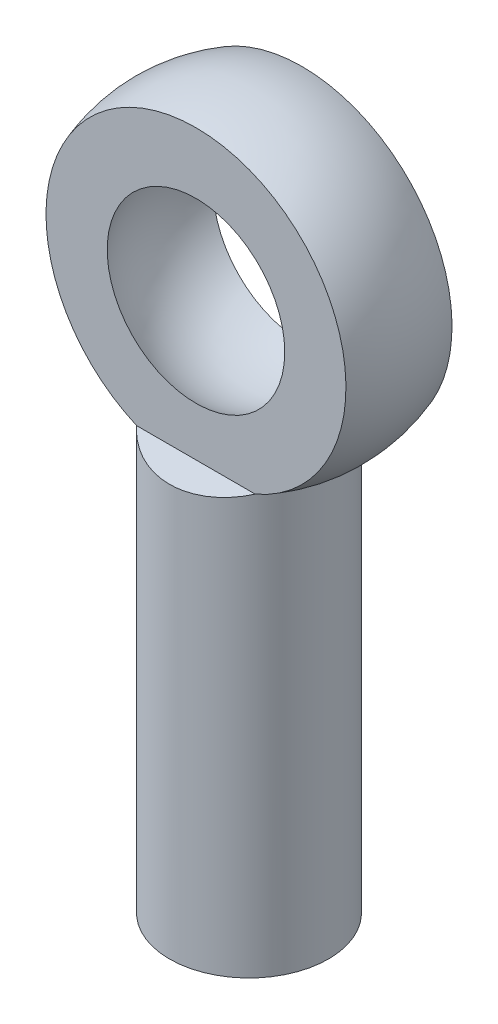
SolidWorks part; units mm, degrees
ref_plane "Front Plane" through (0, 0, 0) normal (0, 0, 1) x (1, 0, 0)
ref_plane "Top Plane" through (0, 0, 0) normal (0, 1, 0) x (1, 0, 0)
ref_plane "Right Plane" through (0, 0, 0) normal (1, 0, 0) x (0, 0, -1)
sketch "Sketch1" plane through (0, 0, 0) normal (0, 1, 0) x (1, 0, 0)
  line L0 (0, 2) -> (0, -2)
  line L1 (0, 0) -> (6, 0) construction
  line L2 (0, 2) -> (5.6569, 2)
  line L3 (0, -2) -> (5.6569, -2)
  arc A0 (5.6569, -2) -> (5.6569, 2) centre (0, 0) ccw
  dimension "D1" = 12
  dimension "D2" = 4
revolve "Revolve1" add sketch "Sketch1" angle 360 about L0
sketch "Sketch3" plane through (0, 0, 0) normal (0, 1, 0) x (1, 0, 0)
  circle A0 centre (0, 0) radius 3
  dimension "D1" = 6
extrude "Boss-Extrude1" add sketch "Sketch3" against normal blind 21
sketch "Sketch4" plane through (0, 0, 0) normal (0, 1, 0) x (1, 0, 0)
  line L0 (0, 3.9) -> (0, -3.9)
  arc A0 (0, -3.9) -> (0, 3.9) centre (0, 0) ccw
  dimension "D1" = 7.8
revolve "Cut-Revolve2" cut sketch "Sketch4" angle 360 about L0
sketch "Sketch5" plane through (0, 0, 0) normal (1, 0, 0) x (0, 0, -1)
  line L1 (-2, -2.492) -> (-3, -2.492) construction
  line L2 (2, -5.1962) -> (3, -5.492)
  line L3 (-2, -2.492) -> (-3, -2.492)
  line L5 (-3, -5.492) -> (-3, -2.492)
  line L7 (-2, -2.492) -> (-2, -5.1962) construction
  line L9 (2, -2.492) -> (2, -5.1962)
  line L10 (-2, -2.492) -> (-2, -5.1962)
  line L11 (3, -5.492) -> (3, -2.492)
  line L12 (-2, -5.1962) -> (-3, -5.492)
  line L13 (0, 0) -> (0, -5.1962) construction
  line L14 (2, -2.492) -> (3, -2.492)
  dimension "D1" = 3
extrude "Cut-Extrude1" cut sketch "Sketch5" against normal mid plane 10
sketch "Sketch6" plane through (0, -21, 0) normal (0, -1, 0) x (1, 0, 0)
  circle A0 centre (0, 0) radius 1.6
  dimension "D1" = 3.2
extrude "Cut-Extrude2" cut sketch "Sketch6" against normal blind 10
